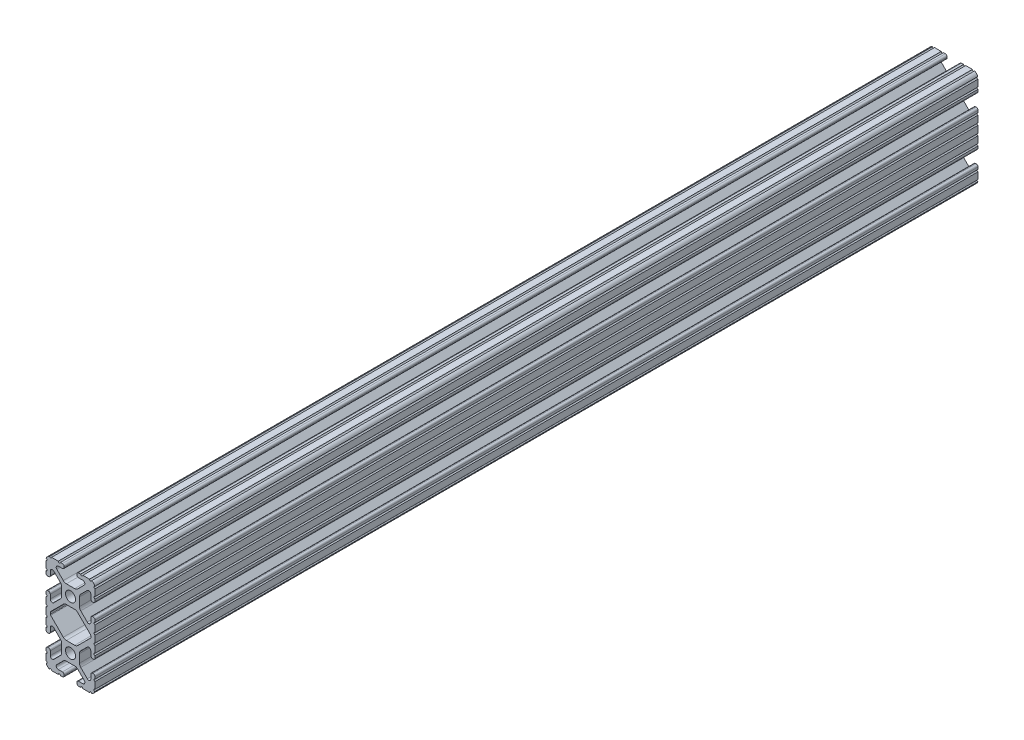
SolidWorks part; units mm, degrees
ref_plane "Front Plane" through (0, 0, 0) normal (0, 0, 1) x (1, 0, 0)
ref_plane "Top Plane" through (0, 0, 0) normal (0, 1, 0) x (1, 0, 0)
ref_plane "Right Plane" through (0, 0, 0) normal (1, 0, 0) x (0, 0, -1)
sketch "Sketch2" plane through (0, 0, 0) normal (0, 0, 1) x (1, 0, 0)
  line L0 (0, 25.4) -> (0, -25.4) construction
  line L1 (-12.7, 0) -> (12.7, 0) construction
  line L2 (3.2512, -25.4) -> (12.7, -25.4)
  line L3 (12.7, -25.4) -> (12.7, -15.9512)
  line L4 (3.2512, -25.4) -> (3.2512, -23.1902)
  line L5 (3.2512, -23.1902) -> (8.9276, -23.1902)
  line L6 (8.9276, -23.1902) -> (3.0856, -17.3482)
  line L7 (0, -12.7) -> (12.7, -25.4) construction
  line L8 (12.7, -15.9512) -> (10.4902, -15.9512)
  line L9 (10.4902, -15.9512) -> (10.4902, -21.6276)
  line L10 (10.4902, -21.6276) -> (4.6482, -15.7856)
  circle A0 centre (0, -12.7) radius 2.6035
  arc A1 (6.3485, -23.1902) -> (7.1039, -21.3665) centre (6.3485, -22.1219) ccw construction
  point P8 (0, -17.3482)
  dimension "Center Hole Diameter" = 5.207
  dimension "Rail Height" = 50.8
  dimension "Rail Width" = 25.4
  dimension "T-Slot Width" = 6.5024
  dimension "Slot Inner Width" = 14.8336
  dimension "Thickness" = 2.2098
  dimension "Slot Depth" = 5.842
  dimension "D1" = 2.2098
  dimension "C to C" = 25.4
sketch "Sketch3" plane through (0, 0, 0) normal (1, 0, 0) x (0, 0, -1)
  line L0 (-228.6, -25.4) -> (228.6, -25.4) construction
  line L1 (-203.2, 0) -> (203.2, 0) construction
  dimension "Length" = 457.2
  dimension "D1" = 25.4
sketch "Sketch4" plane through (0, 0, 0) normal (0, 0, 1) x (1, 0, 0)
  line L0 (4.1904, -25.4) -> (10.1173, -25.4)
  line L1 (3.2512, -25.4) -> (12.7, -25.4) construction
  line L2 (3.2512, -25.4) -> (3.2512, -23.1902) construction
  line L3 (3.2512, -23.1902) -> (8.9276, -23.1902) construction
  line L4 (3.2512, -24.1294) -> (3.2512, -24.4608)
  line L5 (4.1904, -23.1902) -> (6.3485, -23.1902)
  line L6 (0, -17.3482) -> (2.164, -17.3482)
  line L7 (8.9276, -23.1902) -> (3.0856, -17.3482) construction
  line L8 (3.7373, -17.9999) -> (7.1039, -21.3665)
  line L9 (12.7, -25.4) -> (12.7, -15.9512) construction
  line L10 (10.4902, -21.6276) -> (4.6482, -15.7856) construction
  line L11 (10.4902, -15.9512) -> (10.4902, -21.6276) construction
  line L12 (10.4902, -19.0485) -> (10.4902, -16.8904)
  line L13 (12.7, -15.9512) -> (10.4902, -15.9512) construction
  line L14 (11.4294, -15.9512) -> (11.7608, -15.9512)
  line L15 (12.7, -16.8904) -> (12.7, -22.8173)
  line L16 (8.6665, -19.8039) -> (5.2999, -16.4373)
  line L17 (4.6482, -12.7) -> (4.6482, -14.864)
  line L19 (0, -17.3482) -> (0, -15.3035)
  line L20 (0, 25.4) -> (0, -25.4) construction
  line L21 (4.6482, -12.7) -> (2.6035, -12.7)
  arc A0 (3.2512, -24.4608) -> (4.1904, -25.4) centre (4.1904, -24.4608) ccw
  circle A1 centre (0, -12.7) radius 2.6035 construction
  arc A2 (3.2512, -24.1294) -> (4.1904, -23.1902) centre (4.1904, -24.1294) cw
  arc A3 (6.3485, -23.1902) -> (7.1039, -21.3665) centre (6.3485, -22.1219) ccw
  arc A4 (2.164, -17.3482) -> (3.7373, -17.9999) centre (2.164, -19.5732) cw
  arc A5 (10.1173, -25.4) -> (12.7, -22.8173) centre (10.1173, -22.8173) ccw
  arc A6 (8.6665, -19.8039) -> (10.4902, -19.0485) centre (9.4219, -19.0485) ccw
  arc A7 (10.4902, -16.8904) -> (11.4294, -15.9512) centre (11.4294, -16.8904) cw
  arc A8 (11.7608, -15.9512) -> (12.7, -16.8904) centre (11.7608, -16.8904) cw
  arc A9 (5.2999, -16.4373) -> (4.6482, -14.864) centre (6.8732, -14.864) cw
  arc A11 (0, -15.3035) -> (2.6035, -12.7) centre (0, -12.7) ccw
  dimension "D1" = 2.5827
  dimension "D2" = 2.225
  dimension "D3" = 0.9392
extrude "Boss-Extrude1" add sketch "Sketch4" along normal mid plane 457.2
sketch "Sketch5" plane through (0, 0, 0) normal (0, 0, 1) x (1, 0, 0)
  line L0 (3.2512, -25.4) -> (12.7, -25.4) construction
  line L1 (4.1904, -23.1902) -> (6.3485, -23.1902) construction
  line L3 (0, -12.7) -> (12.7, -25.4) construction
  line L4 (6.3485, -23.1902) -> (6.3485, -25.4) construction
  line L5 (8.9276, -23.1902) -> (3.0856, -17.3482) construction
  circle A0 centre (10.3562, -25.4) radius 0.5524
  circle A1 centre (5.796, -25.4) radius 0.5524
  circle A2 centre (12.7, -23.0562) radius 0.5524
  circle A3 centre (12.7, -18.496) radius 0.5524
  point P10 (5.2694, -23.1902)
  point P12 (9.4219, -19.0485)
  dimension "D1" = 1.1049
extrude "Cut-Extrude1" cut sketch "Sketch5" against normal through all both and the other way through all
mirror "Mirror1" about plane through (4.6482, -12.7, 228.6) normal (0, -1, 0) of bodies 137 134
sketch "Sketch6" plane through (0, 0, 0) normal (0, 0, 1) x (1, 0, 0)
  line L0 (12.7, -1.7914) -> (12.7, 0)
  line L1 (12.7, 0) -> (9.8037, 0)
  line L2 (-12.7, 0) -> (12.7, 0) construction
  line L3 (9.8037, 0) -> (9.8037, -2.3438)
  line L4 (9.8037, -2.3438) -> (12.1476, -2.3438)
  circle A0 centre (12.7, -2.3438) radius 0.5524 construction
  arc A1 (12.7, -1.7914) -> (12.1476, -2.3438) centre (12.7, -2.3438) ccw
  arc A4 (12.58, -1.8046) -> (12.7, -2.8963) centre (12.7, -2.3438) ccw construction
  arc A6 (9.8037, 0) -> (10.8954, -0.12) centre (10.3562, 0) ccw construction
extrude "Boss-Extrude2" add sketch "Sketch6" along normal mid plane 457.2
sketch "Sketch7" plane through (0, 0, 0) normal (0, 0, 1) x (1, 0, 0)
  line L0 (5.4206, -5.7168) -> (10.3284, -0.809)
  line L1 (3.7373, -7.4001) -> (7.1039, -4.0335) construction
  line L2 (10.4902, -0.4184) -> (10.4902, 0)
  line L3 (0, 0) -> (10.4902, 0)
  line L4 (-12.7, 0) -> (12.7, 0) construction
  line L5 (0, 0) -> (5.4206, -5.7168)
  arc A0 (10.3284, -0.809) -> (10.4902, -0.4184) centre (9.9377, -0.4184) ccw
  arc A3 (12.7, -1.7914) -> (12.7, -2.8963) centre (12.7, -2.3438) ccw construction
extrude "Cut-Extrude2" cut sketch "Sketch7" against normal through all both and the other way through all
mirror "Mirror2" about plane through (0, 0, 0) normal (0, 1, 0) of bodies 139 135
mirror "Mirror3" about plane through (0, 0, 0) normal (1, 0, 0) of bodies 136
equation "\"D1@Boss-Extrude1\"=\"Length@Sketch3\""
equation "\"D1@Sketch2\"=\"Thickness@Sketch2\""
equation "\"D2@Sketch4\"=\"Slot Inner Width@Sketch2\"*0.15"
equation "\"D1@Sketch4\"=\"D3@Sketch4\"*2.75"
equation "\"D3@Sketch4\"=\"Thickness@Sketch2\"*0.425"
equation "\"D1@Sketch5\"=\"Thickness@Sketch2\"*0.5"
equation "\"D1@Boss-Extrude2\"=\"Length@Sketch3\""
